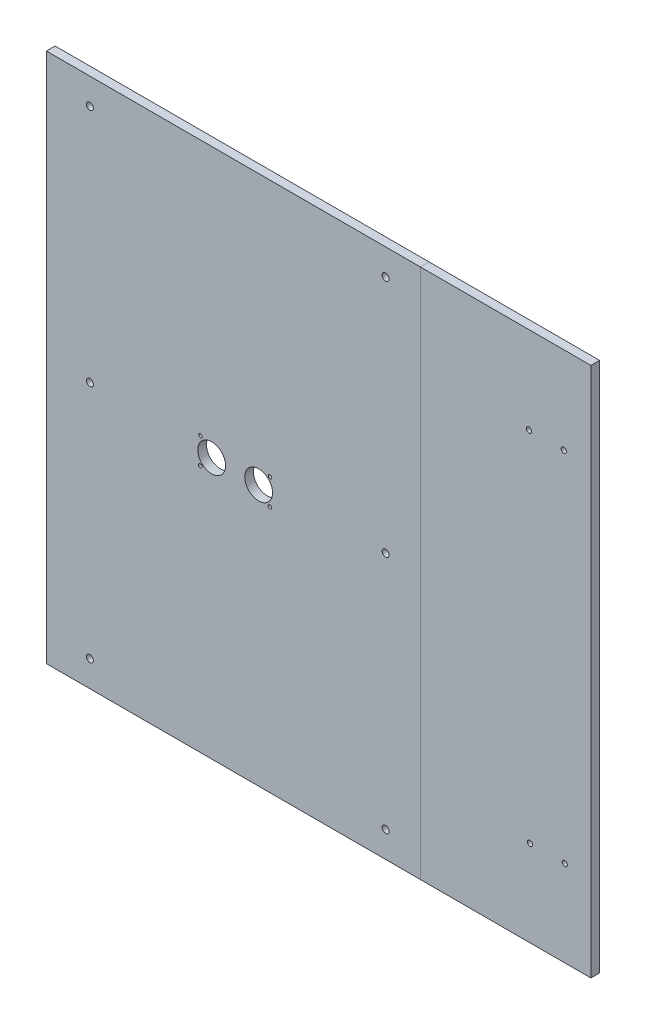
SolidWorks part; units mm, degrees
ref_plane "Plan de face" through (0, 0, 0) normal (0, 0, 1) x (1, 0, 0)
ref_plane "Plan de dessus" through (0, 0, 0) normal (0, 1, 0) x (1, 0, 0)
ref_plane "Plan de droite" through (0, 0, 0) normal (1, 0, 0) x (0, 0, -1)
sketch "Esquisse1" plane through (0, 0, 0) normal (0, 0, 1) x (1, 0, 0)
  line L1 (0, 0) -> (215, 0)
  line L2 (0, 0) -> (0, 305)
  line L3 (0, 305) -> (215, 305)
  line L4 (215, 0) -> (215, 305)
  dimension "D1" = 305
  dimension "D2" = 215
extrude "Boss.-Extru.1" add sketch "Esquisse1" along normal blind 5
sketch "Esquisse2" plane through (0, 0, 0) normal (0, 0, -1) x (-1, 0, 0)
  line L0 (-215, 0) -> (-215, 305) construction
  line L1 (-215, 305) -> (0, 305) construction
  line L2 (0, 305) -> (0, 0) construction
  line L3 (0, 0) -> (-215, 0) construction
  circle A0 centre (-195, 290) radius 2
  circle A1 centre (-25, 290) radius 2
  circle A2 centre (-25, 15) radius 2
  circle A3 centre (-195, 15) radius 2
  circle A4 centre (-195, 152.5) radius 2
  circle A5 centre (-25, 152.5) radius 2
  dimension "D1" = 4
  dimension "D2" = 4
  dimension "D3" = 4
  dimension "D4" = 4
  dimension "D5" = 20
  dimension "D6" = 20
  dimension "D8" = 15
  dimension "D9" = 25
  dimension "D10" = 15
  dimension "D11" = 25
  dimension "D12" = 15
  dimension "D13" = 4
  dimension "D14" = 4
  dimension "D15" = 152.5
  dimension "D16" = 152.5
  dimension "D17" = 20
  dimension "D18" = 25
  dimension "D7" = 15
extrude "Enlèv. mat.-Extru.1" cut sketch "Esquisse2" against normal blind 5
sketch "Esquisse3" plane through (0, 0, 0) normal (0, 0, -1) x (-1, 0, 0)
  line L1 (-215, 305) -> (-313, 305)
  line L2 (-215, 305) -> (-215, 0)
  line L3 (-215, 0) -> (-313, 0)
  line L4 (-313, 305) -> (-313, 0)
  dimension "D1" = 98
extrude "Boss.-Extru.2" add sketch "Esquisse3" against normal blind 5 separate body
sketch "Esquisse4" plane through (0, 0, 0) normal (0, 0, -1) x (-1, 0, 0)
  circle A0 centre (-277.4, 255) radius 1.5
  circle A1 centre (-297.4, 255) radius 1.5
  dimension "D1" = 3
  dimension "D2" = 3
extrude "Enlèv. mat.-Extru.3" cut sketch "Esquisse4" against normal through all
sketch "Esquisse5" plane through (0, 0, 5) normal (0, 0, 1) x (1, 0, 0)
  circle A0 centre (278, 49.5) radius 1.5
  circle A1 centre (298, 49.5) radius 1.5
  dimension "D1" = 3
  dimension "D2" = 3
extrude "Enlèv. mat.-Extru.4" cut sketch "Esquisse5" against normal through all
sketch "Esquisse6" plane through (0, 0, 0) normal (0, 0, -1) x (-1, 0, 0)
  line L0 (0, 305) -> (0, 0) construction
  line L1 (0, 0) -> (-215, 0) construction
  circle A0 centre (-122, 150) radius 8
  circle A1 centre (-95, 150) radius 8
  dimension "D1" = 16
  dimension "D2" = 16
  dimension "D3" = 27
  dimension "D4" = 95
  dimension "D5" = 150
  dimension "D6" = 150
extrude "Enlèv. mat.-Extru.5" cut sketch "Esquisse6" against normal through all
sketch "Esquisse7" plane through (0, 0, 0) normal (0, 0, -1) x (-1, 0, 0)
  circle A0 centre (-128.548, 157.2855) radius 1
  circle A1 centre (-128.452, 142.2855) radius 1
  circle A2 centre (-88.548, 157.7146) radius 1
  circle A3 centre (-88.4519, 142.7146) radius 1
  circle A9 centre (-122, 150) radius 8 construction
  circle A10 centre (-95, 150) radius 8 construction
  dimension "D1" = 2
  dimension "D2" = 2
  dimension "D3" = 2
  dimension "D4" = 2
  dimension "D5" = 15
  dimension "D6" = 15
  dimension "D7" = 34.33
  dimension "D8" = 34.33
  dimension "D9" = 40
  dimension "D10" = 34.33
  dimension "D11" = 34.33
  dimension "D12" = 40
extrude "Enlèv. mat.-Extru.7" cut sketch "Esquisse7" against normal through all
